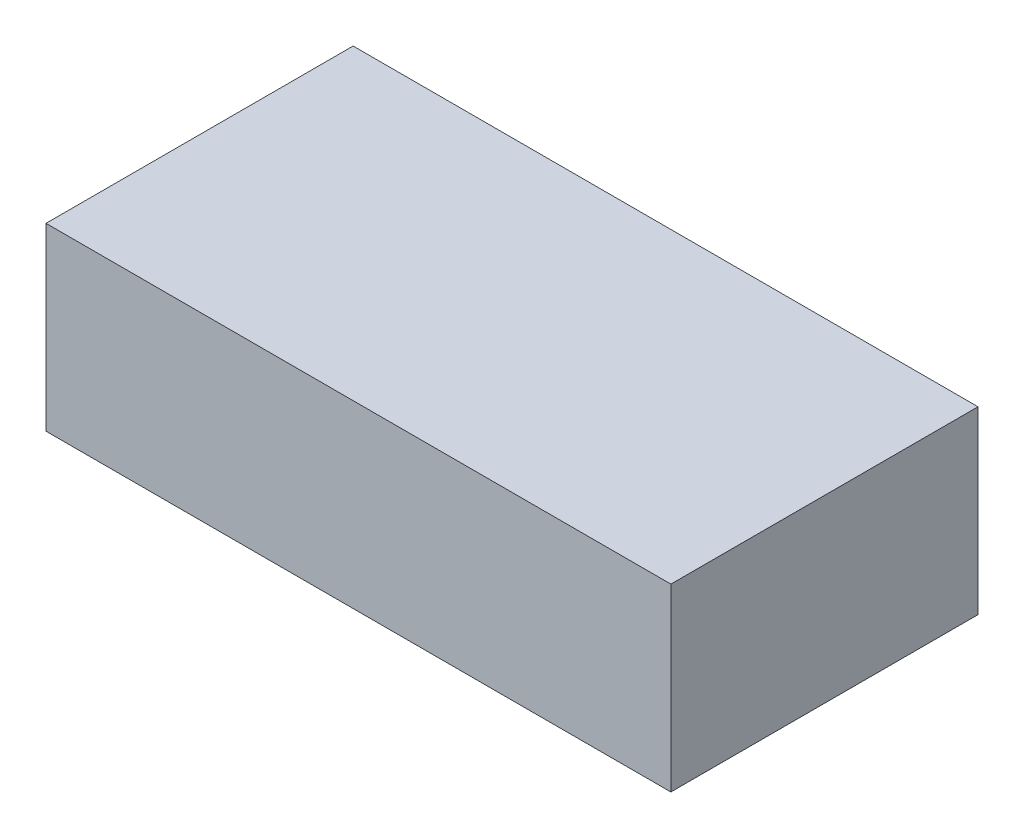
SolidWorks part; units mm, degrees
ref_plane "前视基准面" through (0, 0, 0) normal (0, 0, 1) x (1, 0, 0)
ref_plane "上视基准面" through (0, 0, 0) normal (0, 1, 0) x (1, 0, 0)
ref_plane "右视基准面" through (0, 0, 0) normal (1, 0, 0) x (0, 0, -1)
sketch "草图1" plane through (0, 0, 0) normal (0, 1, 0) x (1, 0, 0)
  line L1 (-59, -29) -> (59, -29)
  line L2 (-59, -29) -> (-59, 29)
  line L3 (-59, 29) -> (59, 29)
  line L4 (59, -29) -> (59, 29)
  line L5 (-59, -29) -> (59, 29) construction
  line L6 (-59, 29) -> (59, -29) construction
  point P0 (0, 0)
  dimension "D1" = 118
  dimension "D2" = 58
extrude "凸台-拉伸1" add sketch "草图1" along normal blind 34
